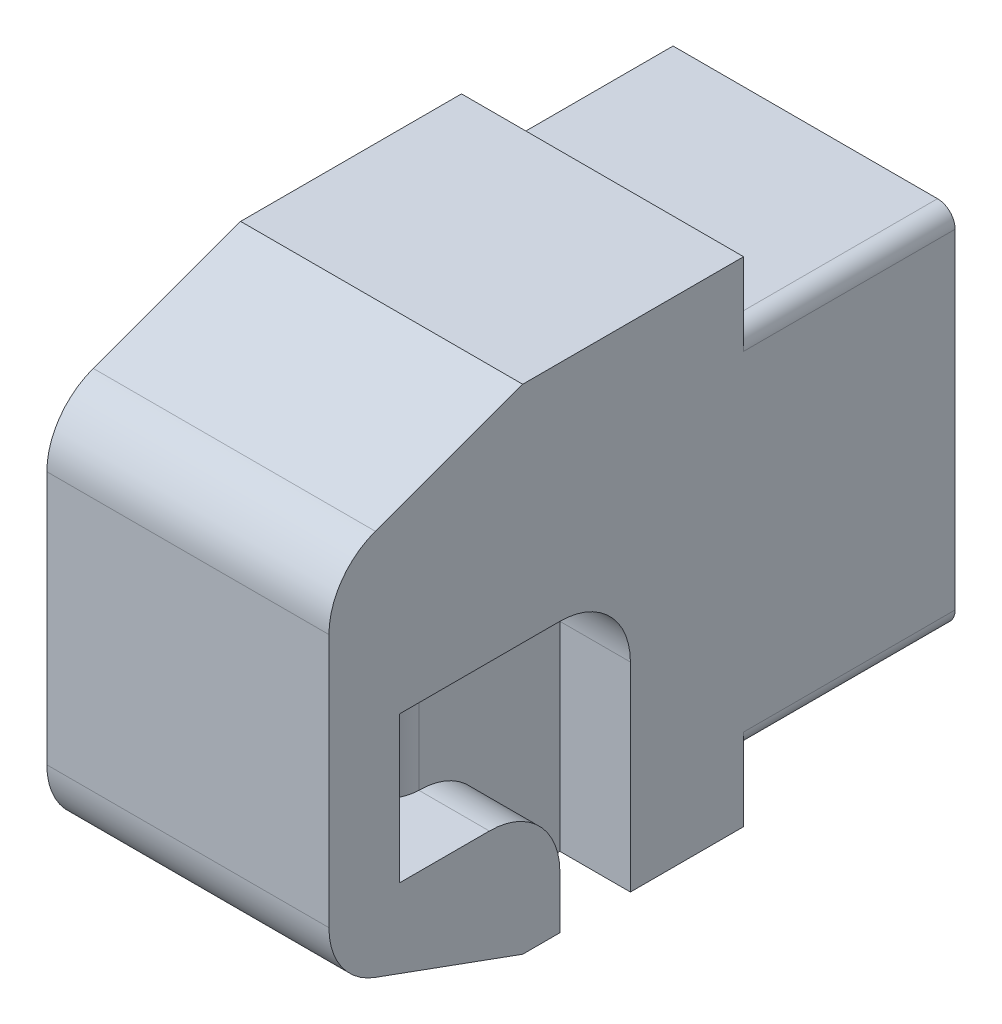
SolidWorks part; units mm, degrees
ref_plane "Front Plane" through (0, 0, 0) normal (0, 0, 1) x (1, 0, 0)
ref_plane "Top Plane" through (0, 0, 0) normal (0, 1, 0) x (1, 0, 0)
ref_plane "Right Plane" through (0, 0, 0) normal (1, 0, 0) x (0, 0, -1)
sketch "Sketch1" plane through (0, 0, 0) normal (0, 0, 1) x (1, 0, 0)
  line L1 (0, 0) -> (8, 0)
  line L2 (0, 0) -> (0, 10.35)
  line L3 (0, 10.35) -> (8, 10.35)
  line L4 (8, 0) -> (8, 10.35)
  dimension "D1" = 8
  dimension "D2" = 10.35
extrude "Boss-Extrude1" add sketch "Sketch1" along normal blind 6
sketch "Sketch2" plane through (0, 0, 6) normal (0, 0, 1) x (1, 0, 0)
  line L1 (0, -1.825) -> (8, -1.825)
  line L2 (0, -1.825) -> (0, 12.175)
  line L3 (0, 12.175) -> (8, 12.175)
  line L4 (8, -1.825) -> (8, 12.175)
  line L7 (0, 10.35) -> (0, 0) construction
  point P7 (0, 5.175)
  point P21 (0, 5.175)
  dimension "D1" = 8
  dimension "D2" = 14
extrude "Boss-Extrude2" add sketch "Sketch2" along normal blind 11.76
sketch "Sketch3" plane through (8, 0, 0) normal (1, 0, 0) x (0, 0, -1)
  line L0 (-17.76, -1.825) -> (-17.76, 12.175) construction
  line L1 (-14.21, 1.675) -> (-15.76, 1.675)
  line L2 (-14.21, 1.675) -> (-14.21, 5.825)
  line L3 (-14.21, 5.825) -> (-15.76, 5.825)
  line L4 (-15.76, 1.675) -> (-15.76, 5.825)
  line L5 (-17.76, -1.825) -> (-6, -1.825) construction
  dimension "D1" = 4.15
  dimension "D2" = 1.55
  dimension "D3" = 2
  dimension "D4" = 3.5
extrude "Cut-Extrude1" cut sketch "Sketch3" against normal blind 6
sketch "Sketch4" plane through (8, 0, 0) normal (1, 0, 0) x (0, 0, -1)
  line L0 (-17.76, -1.825) -> (-6, -1.825) construction
  line L1 (-14.21, 1.675) -> (-11.21, 1.675)
  line L2 (-14.21, 1.675) -> (-14.21, 5.825)
  line L3 (-14.21, 5.825) -> (-9.21, 5.825)
  line L5 (-9.21, -1.825) -> (-11.21, -1.825)
  line L6 (-9.21, -1.825) -> (-9.21, 5.825)
  line L8 (-11.21, -1.825) -> (-11.21, 1.675)
  dimension "D1" = 5
  dimension "D2" = 2
extrude "Cut-Extrude2" cut sketch "Sketch4" against normal blind 2
chamfer "Chamfer1" distance 2 angle 70 1 edges at (4, -1.825, 17.76)
fillet "Fillet1" radius 2 2 edges at (4, 10.175, 17.76) (4, 0.175, 17.76)
fillet "Fillet2" radius 2 2 edges at (7, 5.825, 9.21) (7, 1.675, 11.21)
fillet "Fillet3" radius 1 1 edges at (6, 3.75, 14.21)
chamfer "Chamfer2" [suppressed] distance 1 angle 50
fillet "Fillet5" radius 0.5 2 edges at (8, 10.35, 3) (8, 0, 3)
sketch "Sketch5" plane through (0, 0, 17.76) normal (0, 0, 1) x (1, 0, 0)
  line L0 (0, 5.175) -> (8, 5.175) construction
  line L1 (0, 8.7746) -> (0, 1.5754) construction
  line L2 (8, 1.5754) -> (8, 8.7746) construction
  point P6 (4, 5.175)
  point P7 (11.8462, 10.7168)
ref_plane "Plane1" through (4, 0, 0) normal (1, 0, 0) x (0, 0, -1)
ref_plane "Plane2" through (0, 5.175, 0) normal (0, 1, 0) x (1, 0, 0)
equation "\"D1@Boss-Extrude2\"=10+13-3.08-5-3.16"
